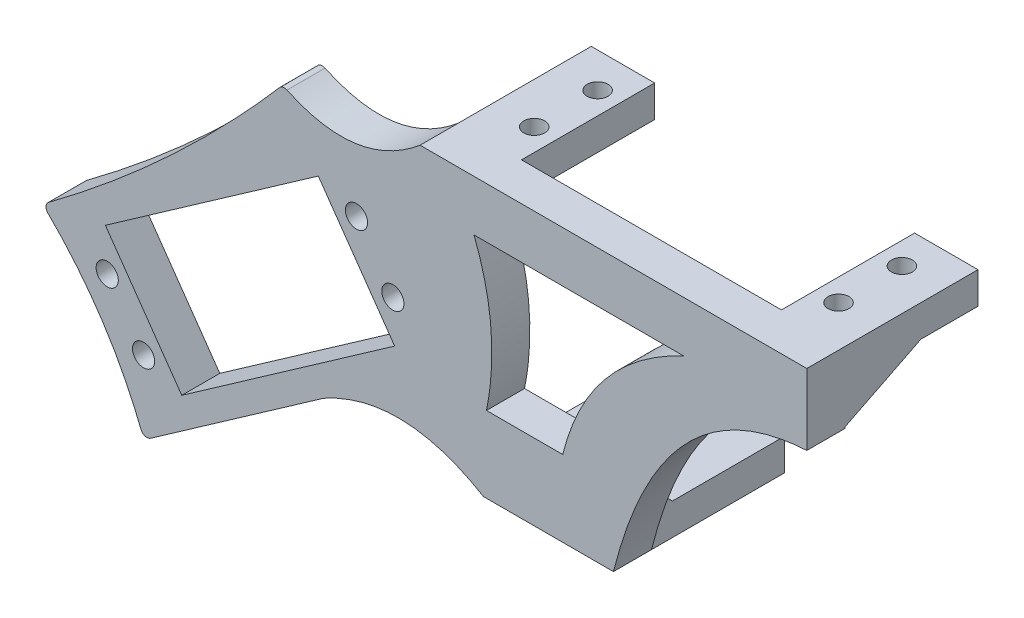
SolidWorks part; units mm, degrees
ref_plane "Front Plane" through (0, 0, 0) normal (0, 0, 1) x (1, 0, 0)
ref_plane "Top Plane" through (0, 0, 0) normal (0, 1, 0) x (1, 0, 0)
ref_plane "Right Plane" through (0, 0, 0) normal (1, 0, 0) x (0, 0, -1)
sketch "Sketch1" plane through (0, 0, 0) normal (0, 0, 1) x (1, 0, 0)
  line L5 (-36.2967, 22.2901) -> (-26.2967, 22.2901)
  line L6 (-36.2967, 22.2901) -> (-36.2967, 17.2901)
  line L7 (-36.2967, 17.2901) -> (-26.2967, 17.2901)
  line L8 (-26.2967, 22.2901) -> (-26.2967, 17.2901)
  line L9 (-36.2967, 22.2901) -> (-26.2967, 17.2901) construction
  line L10 (-36.2967, 17.2901) -> (-26.2967, 22.2901) construction
  line L11 (14.7033, 22.2901) -> (24.7033, 22.2901)
  line L12 (14.7033, 22.2901) -> (14.7033, 17.2901)
  line L13 (14.7033, 17.2901) -> (24.7033, 17.2901)
  line L14 (24.7033, 22.2901) -> (24.7033, 17.2901)
  line L15 (14.7033, 22.2901) -> (24.7033, 17.2901) construction
  line L16 (14.7033, 17.2901) -> (24.7033, 22.2901) construction
  point P0 (-31.2967, 19.7901)
  point P6 (19.7033, 19.7901)
  dimension "D1" = 5
  dimension "D2" = 5
  dimension "D3" = 10
  dimension "D4" = 10
  dimension "D5" = 41
extrude "Boss-Extrude1" add sketch "Sketch1" along normal blind 21
sketch "Sketch2" plane through (0, 0, 21) normal (0, 0, 1) x (1, 0, 0)
  line L0 (-36.2967, 22.2901) -> (24.7033, 22.2901)
  line L1 (24.7033, 22.2901) -> (24.7033, 7.2901)
  line L2 (24.7033, 7.2901) -> (12.7033, 7.2901)
  line L3 (12.7033, 7.2901) -> (-5.7967, -11.2099)
  line L4 (-5.7967, -11.2099) -> (-5.7967, -20.7099)
  line L5 (-5.7967, -20.7099) -> (-36.2967, -20.7099)
  line L6 (-36.2967, -20.7099) -> (-36.2967, 22.2901)
  line L7 (-36.2967, 17.2901) -> (-26.2967, 17.2901) construction
  line L8 (-16.0467, 22.2901) -> (-16.0467, 2.0298) construction
  line L9 (-26.2967, 17.2901) -> (-26.2967, 22.2901) construction
  line L10 (3.5612, 12.2901) -> (-15.7967, -7.0678)
  line L11 (-15.7967, -7.0678) -> (-15.7967, -10.7099)
  line L12 (-15.7967, -10.7099) -> (-26.2967, -10.7099)
  line L13 (-26.2967, -10.7099) -> (-26.2967, 12.2901)
  line L14 (-26.2967, 12.2901) -> (3.5612, 12.2901)
  line L15 (3.5612, 12.2901) -> (3.5612, 12.2901)
  line L16 (3.5612, 12.2901) -> (3.5612, 12.2901)
  dimension "D1" = 38
  dimension "D2" = 15
  dimension "D3" = 10.25
  dimension "D4" = 10.25
  dimension "D5" = 135
  dimension "D6" = 12
  dimension "D7" = 10
extrude "Boss-Extrude2" add sketch "Sketch2" along normal blind 6 contours L6 L0 L1 L2 L3 L4 L5
sketch "Sketch3" plane through (0, 0, 21) normal (0, 0, -1) x (-1, 0, 0)
  line L1 (5.7967, -20.7099) -> (26.2967, -20.7099)
  line L2 (5.7967, -20.7099) -> (5.7967, -15.7099)
  line L3 (5.7967, -15.7099) -> (26.2967, -15.7099)
  line L4 (26.2967, -20.7099) -> (26.2967, -15.7099)
  line L5 (16.0467, 22.2901) -> (16.0467, 17.3696) construction
  line L6 (-14.7033, 22.2901) -> (26.2967, 22.2901) construction
  line L7 (26.2967, 17.2901) -> (26.2967, 22.2901) construction
  line L9 (26.2967, 17.2901) -> (26.2967, 22.2901) construction
  dimension "D1" = 5
  dimension "D2" = 10.25
extrude "Boss-Extrude3" add sketch "Sketch3" along normal blind 21
sketch "Sketch4" plane through (0, 22.2901, 0) normal (0, 1, 0) x (1, 0, 0)
  line L0 (-26.2967, 0) -> (-26.2967, -21) construction
  line L1 (-26.2967, -10.5) -> (-23.5726, -10.5) construction
  line L2 (-26.2967, -21) -> (-26.2967, 0) construction
  circle A0 centre (-29.7967, -5.5) radius 1.65
  circle A1 centre (18.2033, -5.5) radius 1.65
  circle A2 centre (18.2033, -15.5) radius 1.65
  circle A3 centre (-29.7967, -15.5) radius 1.65
  dimension "D1" = 3.3
  dimension "D2" = 3.5
  dimension "D3" = 5
  dimension "D4" = 2
  dimension "D5" = 2
extrude "Cut-Extrude1" cut sketch "Sketch4" against normal up to next
sketch "Sketch5" plane through (0, -15.7099, 0) normal (0, 1, 0) x (1, 0, 0)
  line L0 (-26.2967, 0) -> (-5.7967, 0) construction
  line L1 (-5.7967, 0) -> (-5.7967, -21) construction
  circle A0 centre (-16.0467, -10.5) radius 2.2
  dimension "D1" = 4.4
  dimension "D3" = 10.25
  dimension "D2" = 10.5
extrude "Cut-Extrude2" cut sketch "Sketch5" against normal up to next
sketch "Sketch6" plane through (0, 0, 27) normal (0, 0, 1) x (1, 0, 0)
  line L0 (-36.2967, 22.2901) -> (-36.2967, -20.7099) construction
  line L1 (-85.9329, -13.4688) -> (-52.3477, 10.0479)
  line L2 (-85.9329, -13.4688) -> (-73.8878, -30.671)
  line L3 (-73.8878, -30.671) -> (-40.3026, -7.1543)
  line L4 (-52.3477, 10.0479) -> (-40.3026, -7.1543)
  line L5 (-85.9329, -13.4688) -> (-40.3026, -7.1543) construction
  line L6 (-73.8878, -30.671) -> (-52.3477, 10.0479) construction
  line L7 (-79.8591, -39.7352) -> (-51.5037, -19.8806)
  line L8 (-71.9651, -45.841) -> (-23.4502, -45.841) construction
  line L9 (-79.9104, -22.0699) -> (-76.182, -19.4593) construction
  line L10 (-36.2967, 22.2901) -> (-36.2967, -20.7099)
  line L11 (-36.2967, -20.7099) -> (-5.7967, -20.7099) construction
  circle A0 centre (-85.6453, -19.9816) radius 1.75
  circle A1 centre (-79.9095, -28.1732) radius 1.75
  circle A2 centre (-46.326, 7.55) radius 1.75
  circle A3 centre (-40.5902, -0.6415) radius 1.75
  spline S0 degree 2 poles (-95.8421, -15.5242) (-74.9092, -0.0809) (-57.9628, 19.6612) knots 0 0 0 1 1 1
  spline S1 degree 2 poles (-57.9628, 19.6612) (-46.4471, 13.8149) (-36.2967, 22.2901) knots 0 0 0 1 1 1
  spline S2 degree 2 poles (-95.8421, -15.5242) (-85.0867, -25.7546) (-79.8591, -39.7352) knots 0 0 0 1 1 1
  spline S3 degree 2 poles (-51.5037, -19.8806) (-43.7779, -18.4911) (-36.2967, -20.7099) knots 0 0 0 1 1 1
  point P0 (-63.1177, -10.3116)
  line M9 (-36.2967, 22.2901) -> (-36.2967, -20.7099)
  dimension "D5" = 3.5
  dimension "D8" = 3.5
  dimension "D9" = 3.5
  dimension "D10" = 3.5
  dimension "D1" = 41
  dimension "D2" = 21
  dimension "D3" = 8
  dimension "D4" = 35
  dimension "D6" = 3.5
  dimension "D7" = 5
  dimension "D11" = 3.5
  dimension "D12" = 10
  dimension "D13" = 10
  dimension "D14" = 3.5
  dimension "D15" = 3.5
  dimension "D16" = 5
  dimension "D17" = 4
  dimension "D18" = 4
extrude "Boss-Extrude4" add sketch "Sketch6" against normal up to surface (6 mm away) contours L7 S3 A3 S1 S0 S2 L1 L4 L3 L2 A0 A1 A2 M9 up to face at (-7.5275, 3.4055, 21)
sketch "Sketch7" plane through (0, 0, 21) normal (0, 0, -1) x (-1, 0, 0)
  line L0 (36.2967, -20.7099) -> (26.2967, -20.7099) construction
  line L1 (36.2967, -20.7099) -> (26.2967, -20.7099)
  parabola Q0 (51.5037, -19.8806) -> (36.2967, -20.7099) focus (44.501, -35.4126) apex (43.4171, -19.419) construction
  parabola Q1 (51.5037, -19.8806) -> (36.2967, -20.7099) focus (44.501, -35.4126) apex (43.4171, -19.419)
  spline S0 degree 2 poles (26.2967, -20.7099) (39.1597, -13.0568) (51.5037, -19.8806) knots 0 0 0 1 1 1
extrude "Cut-Extrude3" cut sketch "Sketch7" against normal up to next
sketch "Sketch10" plane through (0, 0, 27) normal (0, 0, 1) x (1, 0, 0)
  line L0 (5.2668, 14.2901) -> (-27.7882, 14.2901)
  line L1 (-36.2967, 22.2901) -> (24.7033, 22.2901) construction
  line L2 (-25.8237, -8.7099) -> (-13.7967, -8.7099)
  line L3 (-5.7967, -11.2099) -> (-5.7967, -20.7099) construction
  line L4 (-5.7967, -20.7099) -> (-26.2967, -20.7099) construction
  spline S2 degree 2 poles (5.2668, 14.2901) (-9.8422, 7.1853) (-13.7967, -8.7099) knots 0 0 0 1 1 1
  spline S3 degree 2 poles (-27.7882, 14.2901) (-23.4314, 3.1329) (-25.8237, -8.7099) knots 0 0 0 1 1 1
  dimension "D1" = 8
  dimension "D2" = 8
  dimension "D3" = 12
extrude "Cut-Extrude7" cut sketch "Sketch10" against normal up to next
sketch "Sketch11" plane through (0, 0, 27) normal (0, 0, 1) x (1, 0, 0)
  line L1 (24.7033, 7.2901) -> (12.7033, 7.2901) construction
  line L2 (12.7033, 7.2901) -> (-5.7967, -11.2099) construction
  line L3 (-5.7967, -11.2099) -> (-5.7967, -20.7099) construction
  line L4 (15.1192, 7.2901) -> (12.7033, 7.2901)
  line L5 (12.7033, 7.2901) -> (-5.7967, -11.2099)
  line L6 (-5.7967, -11.2099) -> (-5.7967, -20.7099)
  spline S0 degree 2 poles (-5.7967, -20.7099) (-0.0669, -3.0227) (15.1192, 7.2901) knots 0 0 0 1 1 1
extrude "Boss-Extrude5" add sketch "Sketch11" against normal up to surface (6 mm away) up to face at (-18.1639, 2.7901, 21)
sketch "Sketch12" plane through (24.7033, 0, 0) normal (1, 0, 0) x (0, 0, -1)
  line L0 (-21, 11.2901) -> (-9, 17.2901)
  line L1 (-21, 17.2901) -> (-21, 7.2901) construction
  line L2 (-21, 17.2901) -> (0, 17.2901) construction
  line L3 (-9, 17.2901) -> (-21, 17.2901)
  line L4 (-21, 17.2901) -> (-21, 11.2901)
  dimension "D1" = 6
  dimension "D2" = 12
extrude "Boss-Extrude6" add sketch "Sketch12" against normal blind 3
sketch "Sketch13" plane through (-36.2967, 0, 0) normal (-1, 0, 0) x (0, 0, 1)
  line L3 (21, 11.2901) -> (21, 17.2901)
  line L4 (21, 17.2901) -> (9, 17.2901)
  line L5 (9, 17.2901) -> (21, 11.2901)
  line L6 (21, 11.2901) -> (21, 17.2901)
  line L7 (21, 17.2901) -> (9, 17.2901)
  line L8 (9, 17.2901) -> (21, 11.2901)
  dimension "D1" = 0
extrude "Boss-Extrude7" add sketch "Sketch13" against normal blind 3
sketch "Sketch14" plane through (-5.7967, 0, 0) normal (1, 0, 0) x (0, 0, -1)
  line L0 (-17.7, -15.7099) -> (-21, -12.4099)
  line L1 (0, -15.7099) -> (-21, -15.7099) construction
  line L2 (-21, -20.7099) -> (-21, 7.2901) construction
  line L3 (-21, -12.4099) -> (-21, -15.7099)
  line L4 (-21, -15.7099) -> (-17.7, -15.7099)
  dimension "D1" = 3.3
  dimension "D2" = 3.3
extrude "Boss-Extrude8" add sketch "Sketch14" against normal up to surface (20.5 mm away) up to face at (-26.2967, -18.2099, 10.5)
sketch "Sketch15" plane through (0, 0, 27) normal (0, 0, 1) x (1, 0, 0)
  line L0 (24.7033, 7.2901) -> (24.7033, 11.0901)
  line L1 (24.7033, 22.2901) -> (24.7033, 7.2901) construction
  line L2 (15.1192, 7.2901) -> (24.7033, 7.2901)
  parabola Q0 (-5.7967, -20.7099) -> (15.1192, 7.2901) focus (23.0101, -19.6791) apex (2.9383, -4.0263) construction
  parabola Q1 (-5.7967, -20.7099) -> (15.1192, 7.2901) focus (23.0101, -19.6791) apex (2.9383, -4.0263)
  spline S1 degree 2 poles (-5.7967, -20.7099) (1.8909, 9.8453) (24.7033, 11.0901) knots 0 0 0 1 1 1
  dimension "D1" = 3.8
  dimension "D2" = 3.5
  dimension "D3" = 3
extrude "Cut-Extrude9" cut sketch "Sketch15" against normal up to surface (6 mm away) contours S1 L0 L2 Q1 up to face at (-18.1639, 2.7901, 21)
fillet "Fillet1" radius 1 3 edges at (-95.8421, -15.5242, 24) (-57.9628, 19.6612, 24) (-79.8591, -39.7352, 24)
sketch "Sketch16" plane through (0, -15.7099, 0) normal (0, 1, 0) x (1, 0, 0)
  line L0 (-26.2967, 0) -> (-5.7967, 0) construction
  line L1 (-13.9105, -6.8) -> (-18.1829, -6.8)
  line L2 (-18.1829, -6.8) -> (-20.3191, -10.5)
  line L3 (-20.3191, -10.5) -> (-18.1829, -14.2)
  line L4 (-18.1829, -14.2) -> (-13.9105, -14.2)
  line L5 (-13.9105, -14.2) -> (-11.7743, -10.5)
  line L6 (-11.7743, -10.5) -> (-13.9105, -6.8)
  circle A0 centre (-16.0467, -10.5) radius 3.7 construction
  dimension "D1" = 7.4
extrude "Cut-Extrude10" cut sketch "Sketch16" against normal blind 2
